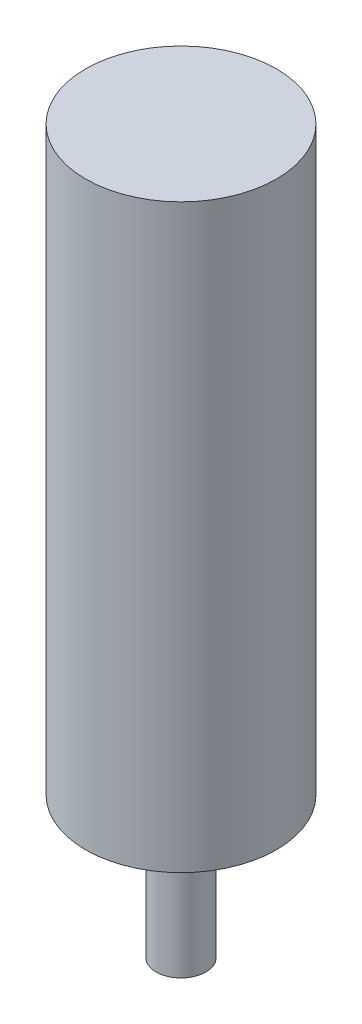
SolidWorks part; units mm, degrees
material "AISI 1020"
ref_plane "Front Plane" through (0, 0, 0) normal (0, 0, 1) x (1, 0, 0)
ref_plane "Top Plane" through (0, 0, 0) normal (0, 1, 0) x (1, 0, 0)
ref_plane "Right Plane" through (0, 0, 0) normal (1, 0, 0) x (0, 0, -1)
sketch "Sketch1" plane through (0, 0, 0) normal (0, 1, 0) x (1, 0, 0)
  circle A0 centre (0, 0) radius 11.5
  dimension "D1" = 23
extrude "Extrude1" add sketch "Sketch1" along normal blind 70
sketch "Sketch2" plane through (0, 0, 0) normal (0, -1, 0) x (1, 0, 0)
  circle A0 centre (0, 0) radius 7.5
  dimension "D2" = 15
extrude "Extrude2" add sketch "Sketch2" along normal blind 1
sketch "Sketch3" plane through (0, -1, 0) normal (0, -1, 0) x (1, 0, 0)
  circle A0 centre (0, 0) radius 3
  dimension "D2" = 6
extrude "Extrude3" add sketch "Sketch3" along normal blind 16
